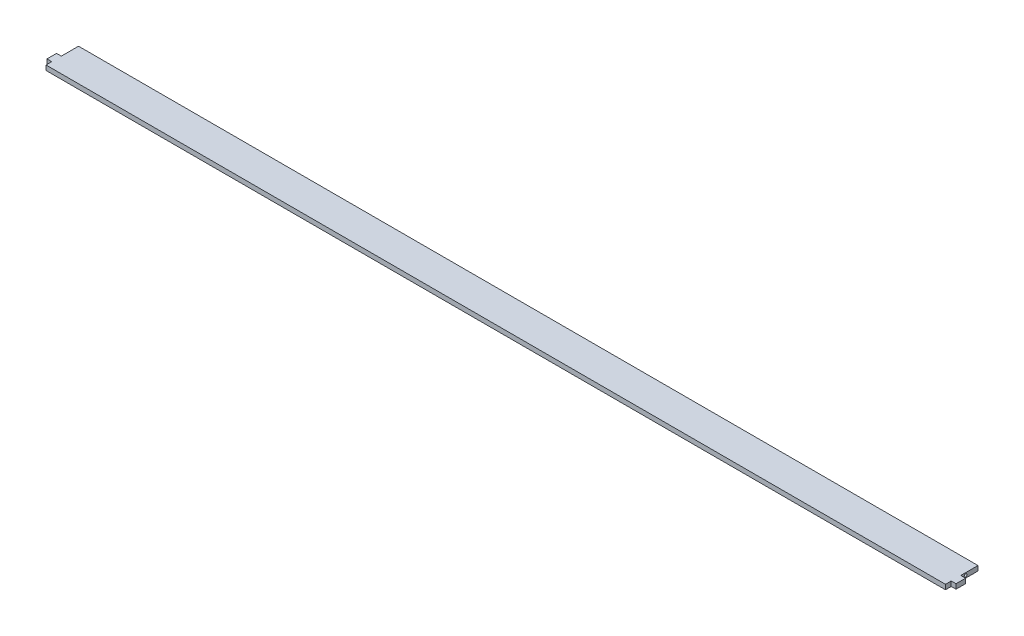
SolidWorks part; units mm, degrees
ref_plane "Front Plane" through (0, 0, 0) normal (0, 0, 1) x (1, 0, 0)
ref_plane "Top Plane" through (0, 0, 0) normal (0, 1, 0) x (1, 0, 0)
ref_plane "Right Plane" through (0, 0, 0) normal (1, 0, 0) x (0, 0, -1)
sketch "Sketch1" plane through (0, 0, 0) normal (0, 1, 0) x (1, 0, 0)
  line L0 (-298.45, -6.2457) -> (-298.45, -10.0557)
  line L1 (298.45, 11.5343) -> (-298.45, 11.5343)
  line L2 (298.45, 11.5343) -> (298.45, 0.1043)
  line L4 (-298.45, 11.5343) -> (-298.45, 0.1043)
  line L5 (-298.45, 0.1043) -> (-301.625, 0.1043)
  line L6 (0, -10.0557) -> (0, 0) construction
  line L7 (-298.45, -6.2457) -> (-301.625, -6.2457)
  line L8 (-301.625, 0.1043) -> (-301.625, -6.2457)
  line L9 (301.625, 0.1043) -> (301.625, -6.2457)
  line L10 (298.45, -6.2457) -> (301.625, -6.2457)
  line L11 (298.45, 0.1043) -> (301.625, 0.1043)
  line L12 (298.45, -6.2457) -> (298.45, -10.0557)
  line L13 (-298.45, -10.0557) -> (298.45, -10.0557)
  dimension "D1" = 596.9
  dimension "D2" = 298.45
  dimension "D4" = 3.175
  dimension "D5" = 6.35
extrude "Boss-Extrude1" add sketch "Sketch1" along normal blind 3.175
sketch "Sketch2" plane through (-298.45, 0, 0) normal (-1, 0, 0) x (0, 0, 1)
  circle A0 centre (-3.2793, 1.5875) radius 0.889
  dimension "D1" = 1.778
extrude "Cut-Extrude1" cut sketch "Sketch2" against normal blind 6.35
mirror "Mirror1" about plane through (0, 0, 0) normal (1, 0, 0) of "Cut-Extrude1"
equation "\"D2@Sketch1\" = \"D1@Sketch1\"/2"
